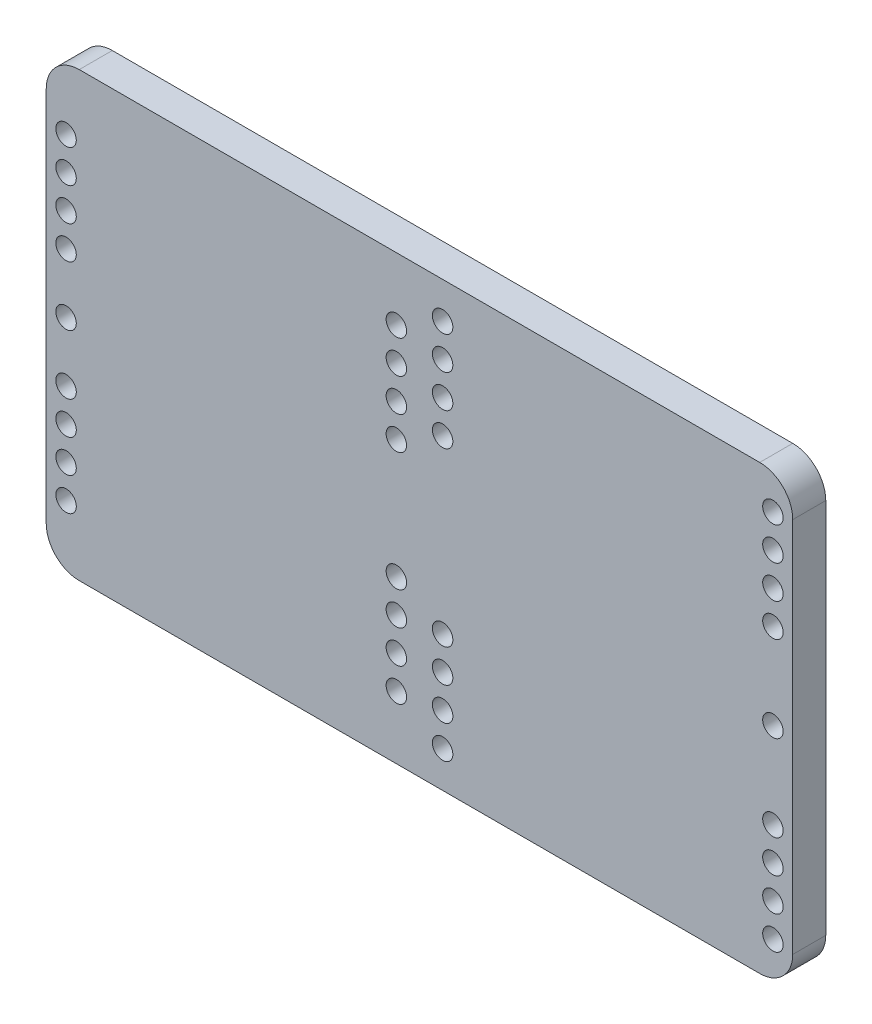
SolidWorks part; units mm, degrees
ref_plane "前视基准面" through (0, 0, 0) normal (0, 0, 1) x (1, 0, 0)
ref_plane "上视基准面" through (0, 0, 0) normal (0, 1, 0) x (1, 0, 0)
ref_plane "右视基准面" through (0, 0, 0) normal (1, 0, 0) x (0, 0, -1)
other "Configuration Table"
sketch "草图1" plane through (0, 0, 0) normal (0, 0, 1) x (1, 0, 0)
  line L0 (0, 33.5) -> (113, 33.5) construction
  line L1 (5, 0) -> (108, 0)
  line L2 (0, 5) -> (0, 62)
  line L3 (5, 67) -> (108, 67)
  line L4 (113, 5) -> (113, 62)
  line L5 (56.5, 67) -> (56.5, 0) construction
  line L6 (3, 42.5) -> (3, 33.5) construction
  line L7 (3, 42.5) -> (3, 47.5) construction
  line L8 (28, 67) -> (28, 0) construction
  line L9 (110, 33.5) -> (110, 46.5) construction
  line L10 (110, 46.5) -> (110, 51.5) construction
  line L11 (85, 71.7037) -> (85, -11.6619) construction
  arc A0 (108, 67) -> (113, 62) centre (108, 62) cw
  arc A1 (108, 0) -> (113, 5) centre (108, 5) ccw
  arc A2 (5, 0) -> (0, 5) centre (5, 5) cw
  arc A3 (0, 62) -> (5, 67) centre (5, 62) cw
  circle A4 centre (3, 33.5) radius 1.55
  circle A5 centre (110, 33.5) radius 1.55
  circle A6 centre (3, 42.5) radius 1.55
  circle A7 centre (3, 47.5) radius 1.55
  circle A8 centre (3, 52.5) radius 1.55
  circle A9 centre (3, 57.5) radius 1.55
  circle A10 centre (3, 24.5) radius 1.55
  circle A11 centre (3, 19.5) radius 1.55
  circle A12 centre (3, 14.5) radius 1.55
  circle A13 centre (3, 9.5) radius 1.55
  circle A14 centre (53, 9.5) radius 1.55
  circle A15 centre (53, 14.5) radius 1.55
  circle A16 centre (53, 19.5) radius 1.55
  circle A17 centre (53, 24.5) radius 1.55
  circle A18 centre (53, 42.5) radius 1.55
  circle A19 centre (53, 47.5) radius 1.55
  circle A20 centre (53, 52.5) radius 1.55
  circle A21 centre (53, 57.5) radius 1.55
  circle A22 centre (110, 46.5) radius 1.55
  circle A23 centre (110, 51.5) radius 1.55
  circle A24 centre (110, 56.5) radius 1.55
  circle A25 centre (110, 61.5) radius 1.55
  circle A26 centre (110, 20.5) radius 1.55
  circle A27 centre (110, 15.5) radius 1.55
  circle A28 centre (110, 10.5) radius 1.55
  circle A29 centre (110, 5.5) radius 1.55
  circle A30 centre (60, 61.5) radius 1.55
  circle A31 centre (60, 56.5) radius 1.55
  circle A32 centre (60, 46.5) radius 1.55
  circle A33 centre (60, 51.5) radius 1.55
  circle A34 centre (60, 20.5) radius 1.55
  circle A35 centre (60, 15.5) radius 1.55
  circle A36 centre (60, 10.5) radius 1.55
  circle A37 centre (60, 5.5) radius 1.55
  point P7 (113, 67)
  point P10 (113, 0)
  point P13 (0, 0)
  point P16 (0, 67)
  point P81 (0, 0)
  dimension "D3" = 5
  dimension "D4" = 3.1
  dimension "D5" = 3
  dimension "D7" = 3.1
  dimension "D11" = 3.1
  dimension "D1" = 113
  dimension "D2" = 67
  dimension "D6" = 9
  dimension "D8" = 5
  dimension "D10" = 25
  dimension "D12" = 13
  dimension "D13" = 5
  dimension "D15" = 25
  dimension "D9" = 4
  dimension "D14" = 4
extrude "凸台-拉伸2" add sketch "草图1" along normal blind 5
